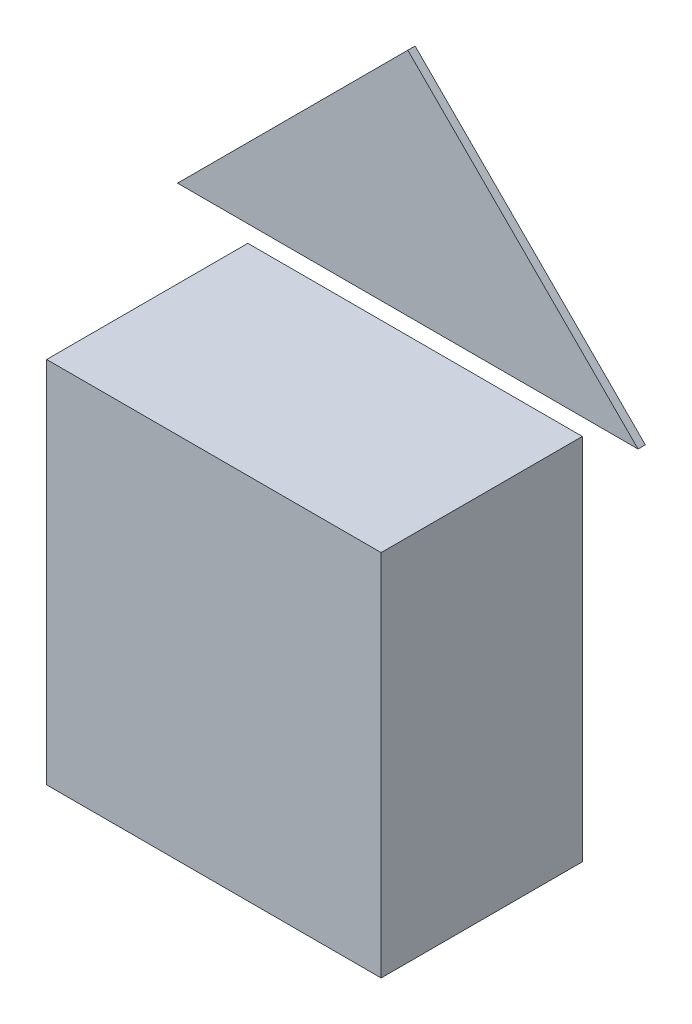
SolidWorks part; units mm, degrees
ref_plane "Front Plane" through (0, 0, 0) normal (0, 0, 1) x (1, 0, 0)
ref_plane "Top Plane" through (0, 0, 0) normal (0, 1, 0) x (1, 0, 0)
ref_plane "Right Plane" through (0, 0, 0) normal (1, 0, 0) x (0, 0, -1)
sketch "Sketch2" plane through (0, 0, 0) normal (0, 0, 1) x (1, 0, 0)
  line L0 (23.2626, 532.4408) -> (-1276.7374, 532.4408)
  line L1 (-666.7374, 782.4408) -> (713.2626, 782.4408)
  line L2 (-666.7374, 782.4408) -> (-666.7374, -737.5592)
  line L3 (-666.7374, -737.5592) -> (713.2626, -737.5592)
  line L4 (713.2626, 782.4408) -> (713.2626, -737.5592)
  line L5 (-766.7374, 882.4408) -> (813.2626, 882.4408)
  line L6 (-766.7374, 882.4408) -> (-766.7374, -837.5592)
  line L7 (-766.7374, -837.5592) -> (813.2626, -837.5592)
  line L8 (813.2626, 882.4408) -> (813.2626, -837.5592)
  line L9 (-1276.7374, 532.4408) -> (1323.2626, 532.4408)
  line L10 (23.2626, 1832.4408) -> (-926.7374, 882.4408)
  line L11 (-926.7374, 882.4408) -> (973.2626, 882.4408)
  line L12 (973.2626, 882.4408) -> (23.2626, 1832.4408)
  line L14 (520.278, 882.4408) -> (-590.1646, 882.4408)
  line L15 (-413.8893, 882.4408) -> (460.4144, 882.4408)
  line L16 (-413.8893, 882.4408) -> (-413.8893, 1756.7358)
  line L17 (-413.8893, 1756.7358) -> (460.4144, 1756.7358)
  line L18 (460.4144, 882.4408) -> (460.4144, 1756.7358)
  circle A0 centre (23.2626, 532.4408) radius 100
  circle A1 centre (23.2626, 532.4408) radius 1300
  dimension "D9" = 2600
  dimension "D12" = 200
  dimension "D1" = 1380
  dimension "D2" = 1520
  dimension "D3" = 100
  dimension "D4" = 100
  dimension "D5" = 100
  dimension "D6" = 100
  dimension "D7" = 250
  dimension "D8" = 690
  dimension "D11" = 45
  dimension "D14" = 874.295
  dimension "D15" = 874.3037
sketch "Sketch3" plane through (0, 0, 0) normal (0, 0, 1) x (1, 0, 0)
  line L0 (23.2626, 532.4408) -> (-1276.7374, 532.4408)
  line L1 (-666.7374, 782.4408) -> (713.2626, 782.4408)
  line L2 (-666.7374, 782.4408) -> (-666.7374, -737.5592)
  line L3 (-666.7374, -737.5592) -> (713.2626, -737.5592)
  line L4 (713.2626, 782.4408) -> (713.2626, -737.5592)
  line L5 (-766.7374, 882.4408) -> (813.2626, 882.4408)
  line L6 (-766.7374, 882.4408) -> (-766.7374, -837.5592)
  line L7 (-766.7374, -837.5592) -> (813.2626, -837.5592)
  line L8 (813.2626, 882.4408) -> (813.2626, -837.5592)
  line L9 (-1276.7374, 532.4408) -> (1323.2626, 532.4408)
  line L10 (23.2626, 1832.4408) -> (-926.7374, 882.4408)
  line L11 (-926.7374, 882.4408) -> (973.2626, 882.4408)
  line L12 (973.2626, 882.4408) -> (23.2626, 1832.4408)
  line L14 (520.278, 882.4408) -> (-590.1646, 882.4408)
  line L15 (-413.8893, 882.4408) -> (460.4144, 882.4408)
  line L16 (-413.8893, 882.4408) -> (-413.8893, 1756.7358)
  line L17 (-413.8893, 1756.7358) -> (460.4144, 1756.7358)
  line L18 (460.4144, 882.4408) -> (460.4144, 1756.7358)
  circle A0 centre (23.2626, 532.4408) radius 100
  circle A1 centre (23.2626, 532.4408) radius 1300
  dimension "D9" = 2600
  dimension "D12" = 200
  dimension "D1" = 1380
  dimension "D2" = 1520
  dimension "D3" = 100
  dimension "D4" = 100
  dimension "D5" = 100
  dimension "D6" = 100
  dimension "D7" = 250
  dimension "D8" = 690
  dimension "D11" = 45
  dimension "D14" = 874.295
  dimension "D15" = 874.3037
extrude "Boss-Extrude3" add sketch "Sketch2" along normal blind 830 contours L2 L3 L4 L1
extrude "Boss-Extrude5" add sketch "Sketch3" along normal blind 30 separate body contours L10 L11 L12
